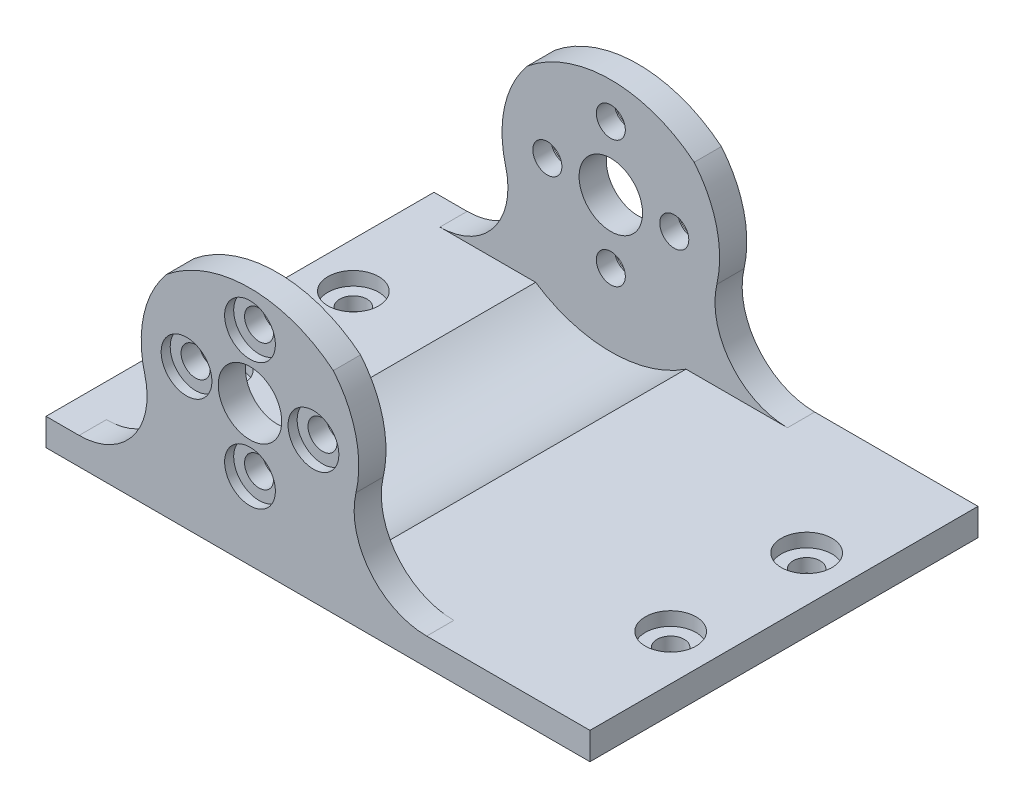
SolidWorks part; units mm, degrees
ref_plane "前视基准面" through (0, 0, 0) normal (0, 0, 1) x (1, 0, 0)
ref_plane "上视基准面" through (0, 0, 0) normal (0, 1, 0) x (1, 0, 0)
ref_plane "右视基准面" through (0, 0, 0) normal (1, 0, 0) x (0, 0, -1)
other "Configuration Table"
sketch "草图1" plane through (0, 0, 0) normal (0, 0, 1) x (1, 0, 0)
  circle A0 centre (0, 0) radius 13
  dimension "D1" = 26
extrude "凸台-拉伸1" add sketch "草图1" along normal blind 42.8
sketch "草图2" plane through (0, 0, 42.8) normal (0, 0, 1) x (1, 0, 0)
  circle A0 centre (0, 0) radius 3.5
  dimension "D1" = 7
extrude "切除-拉伸1" cut sketch "草图2" against normal through all
sketch "草图4" plane through (0, 0, 0) normal (0, 0, -1) x (-1, 0, 0)
  circle A0 centre (0, 0) radius 7 construction
  circle A1 centre (0, 7) radius 1.6
  circle A2 centre (7, 0) radius 1.6
  circle A3 centre (0, -7) radius 1.6
  circle A4 centre (-7, 0) radius 1.6
  point P14 (0, 0)
  dimension "D1" = 14
  dimension "D2" = 3.2
  dimension "D3" = 4
extrude "切除-拉伸2" cut sketch "草图4" against normal through all
sketch "草图5" plane through (0, 0, 0) normal (0, 0, -1) x (-1, 0, 0)
  line L0 (-12.5, 0) -> (-12.5, -12.5) construction
  line L1 (-12.5, -12.5) -> (-37.5, -12.5)
  line L2 (-37.5, -12.5) -> (-37.5, -15.5)
  line L3 (-37.5, -15.5) -> (22.5, -15.5)
  line L4 (22.5, -15.5) -> (22.5, -12.5)
  line L6 (12.5, 0) -> (12.5, -12.5) construction
  line L7 (12.5, -12.5) -> (22.5, -12.5)
  circle A0 centre (0, 0) radius 12.5
  arc A1 (-25, -12.5) -> (-12.5, 0) centre (-25, 0) ccw
  arc A2 (12.5, 0) -> (22.5, -12.5) centre (25.3125, 0) ccw
  dimension "D1" = 25
  dimension "D5" = 12.5
  dimension "D2" = 3
  dimension "D3" = 25
  dimension "D4" = 10
extrude "凸台-拉伸2" add sketch "草图5" against normal up to surface (42.8 mm away) up to face at (-1.6, 7, 42.8)
sketch "草图7" plane through (0, 0, 0) normal (0, 0, -1) x (-1, 0, 0)
  line L4 (-25, -12.5) -> (-37.5, -12.5)
  line L5 (-37.5, -12.5) -> (-37.5, -15.5)
  line L6 (-37.5, -15.5) -> (22.5, -15.5)
  line L7 (22.5, -15.5) -> (22.5, -12.5)
  arc A0 (12.5, 0) -> (-12.5, 0) centre (0, 0) ccw
  arc A1 (-12.755, -2.512) -> (-12.5, 0) centre (-25, 0) ccw
  arc A2 (12.5, 0) -> (12.7519, -2.5279) centre (25.3125, 0) ccw
  arc A4 (12.7519, -2.5279) -> (-12.755, -2.512) centre (0, 0) ccw
  arc A5 (-25, -12.5) -> (-12.755, -2.512) centre (-25, 0) ccw
  arc A6 (12.7519, -2.5279) -> (22.5, -12.5) centre (25.3125, 0) ccw
  arc A7 (12.7519, -2.5279) -> (-12.755, -2.512) centre (0, 0) ccw
  dimension "D1" = 25
  dimension "D2" = 0
extrude "切除-拉伸3" cut sketch "草图7" against normal up to surface (42.8 mm away) contours A7 A1 A0 A2 up to face at (-1.6, 7, 42.8)
ref_plane "基准面1" through (0, 0, 21.4) normal (0, 0, 1) x (1, 0, 0)
sketch "草图8" plane through (0, 0, 21.4) normal (0, 0, 1) x (1, 0, 0)
  line L2 (-22.5, -12.5) -> (25, -12.5) construction
  line L3 (0, -12.5) -> (-22.5, -12.5)
  line L4 (0, -12.5) -> (25, -12.5)
  line L7 (-22.5, -12.5) -> (-22.5, -15.5)
  line L8 (-22.5, -15.5) -> (37.5, -15.5)
  line L9 (37.5, -15.5) -> (37.5, -12.5)
  line L10 (37.5, -12.5) -> (25, -12.5)
  circle A0 centre (0, 0) radius 12.5
  arc A1 (12.5, 0) -> (25, -12.5) centre (25, 0) ccw construction
  arc A2 (-22.5, -12.5) -> (-12.5, 0) centre (-25.3125, 0) ccw construction
  arc A6 (12.5, 0) -> (25, -12.5) centre (25, 0) ccw
  arc A7 (12.5, 0) -> (-12.5, 0) centre (0, 0) ccw
  arc A8 (-22.5, -12.5) -> (-12.5, 0) centre (-25.3125, 0) ccw
  arc A9 (12.5, 0) -> (25, -12.5) centre (25, 0) ccw
  arc A10 (12.5, 0) -> (-12.5, 0) centre (0, 0) ccw
  arc A11 (-22.5, -12.5) -> (-12.5, 0) centre (-25.3125, 0) ccw
  dimension "D2" = 25
  dimension "D4" = 0
extrude "切除-拉伸4" cut sketch "草图8" against normal offset from surface 3 and the other way offset from surface (18.4 mm away) 3 up to face at (-1.6, 7, 0) other way up to face at (7.8005, -8.6204, 42.8)
sketch "草图9" plane through (0, -12.5, 0) normal (0, 1, 0) x (1, 0, 0)
  line L0 (37.5, -21.4) -> (32.5, -21.4) construction
  line L1 (37.5, -42.8) -> (37.5, 0) construction
  line L3 (32.5, -13.9) -> (32.5, -28.9) construction
  line L4 (-22.5, -21.4) -> (-17.5, -21.4) construction
  line L6 (-17.5, -28.9) -> (-17.5, -13.9) construction
  circle A0 centre (32.5, -13.9) radius 1.5
  circle A1 centre (32.5, -28.9) radius 1.5
  circle A2 centre (-17.5, -13.9) radius 1.5
  circle A3 centre (-17.5, -28.9) radius 1.5
  point P9 (32.5, -21.4)
  point P18 (-17.5, -21.4)
  dimension "D3" = 3
  dimension "D4" = 3
  dimension "D7" = 3
  dimension "D8" = 3
  dimension "D1" = 15
  dimension "D2" = 5
  dimension "D5" = 15
  dimension "D6" = 5
extrude "切除-拉伸5" cut sketch "草图9" against normal through all both and the other way through all
sketch "草图10" plane through (0, -12.5, 0) normal (0, 1, 0) x (1, 0, 0)
  circle A0 centre (-17.5, -13.9) radius 2.8
  circle A1 centre (-17.5, -28.9) radius 2.8
  circle A2 centre (32.5, -13.9) radius 2.8
  circle A3 centre (32.5, -28.9) radius 2.8
  dimension "D1" = 5.6
  dimension "D2" = 5.6
  dimension "D3" = 5.6
  dimension "D4" = 5.6
extrude "切除-拉伸6" cut sketch "草图10" against normal blind 1.5 and the other way through all
sketch "草图11" plane through (0, 0, 0) normal (0, 0, -1) x (-1, 0, 0)
  circle A0 centre (0, 7) radius 2.8
  circle A1 centre (7, 0) radius 2.8
  circle A2 centre (0, -7) radius 2.8
  circle A3 centre (-7, 0) radius 2.8
  dimension "D1" = 5.6
  dimension "D2" = 5.6
  dimension "D3" = 5.6
  dimension "D4" = 5.6
extrude "切除-拉伸7" cut sketch "草图11" against normal blind 1
mirror "镜向1" about plane through (0, 0, 21.4) normal (0, 0, 1) of "切除-拉伸7"
sketch "草图12" plane through (0, 0, 21.4) normal (0, 0, 1) x (1, 0, 0)
  line L1 (-22.5, -12.5) -> (25, -12.5)
  line L2 (-8.2916, -12.5) -> (8.2916, -12.5)
  arc A0 (-13.858, -5.7407) -> (13.875, -5.6995) centre (0, 0) ccw
  arc A4 (12.5, 0) -> (-12.5, 0) centre (0, 0) ccw
  arc A5 (-22.5, -12.5) -> (-12.5, 0) centre (-25.3125, 0) ccw
  arc A6 (12.5, 0) -> (25, -12.5) centre (25, 0) ccw
  arc A7 (12.5, 0) -> (-12.5, 0) centre (0, 0) ccw
  arc A8 (-13.858, -5.7407) -> (-12.5, 0) centre (-25.3125, 0) ccw
  arc A9 (12.5, 0) -> (13.875, -5.6995) centre (25, 0) ccw
  dimension "D1" = 30
  dimension "D2" = 0
extrude "切除-拉伸8" cut sketch "草图12" against normal up to surface and the other way up to surface contours L2 A0 up to face at (0.5259, -4.2107, 3) other way up to face at (8.6, 0, 39.8)
sketch "草图13" plane through (0, 0, 0) normal (0, 0, -1) x (-1, 0, 0)
  line L0 (0, 0) -> (0, -7) construction
  line L4 (-25, -12.5) -> (-37.5, -12.5)
  line L5 (-37.5, -12.5) -> (-37.5, -15.5)
  line L6 (-37.5, -15.5) -> (22.5, -15.5)
  line L7 (22.5, -15.5) -> (22.5, -12.5)
  arc A0 (10.9853, 5.9643) -> (-10.9853, 5.9643) centre (0, -3.5) ccw
  circle A1 centre (0, 0) radius 3.5 construction
  arc A5 (12.5, 0) -> (-12.5, 0) centre (0, 0) ccw
  arc A6 (-25, -12.5) -> (-12.5, 0) centre (-25, 0) ccw
  arc A7 (12.5, 0) -> (22.5, -12.5) centre (25.3125, 0) ccw
  arc A8 (10.9853, 5.9643) -> (-10.9853, 5.9643) centre (0, 0) ccw
  point P16 (0, -3.5)
  dimension "D1" = 29
  dimension "D2" = 0
extrude "切除-拉伸9" cut sketch "草图13" against normal through all
sketch "草图14" plane through (0, 0, 42.8) normal (0, 0, 1) x (1, 0, 0)
  line L0 (-22.5, -12.5) -> (25, -12.5)
  line L4 (-22.5, -12.5) -> (-22.5, -15.5)
  line L5 (-22.5, -15.5) -> (37.5, -15.5)
  line L6 (37.5, -15.5) -> (37.5, -12.5)
  line L7 (37.5, -12.5) -> (25, -12.5)
  line L8 (-22.5, -12.5) -> (-22.5, -15.5)
  line L9 (-22.5, -15.5) -> (37.5, -15.5)
  line L10 (37.5, -15.5) -> (37.5, -12.5)
  line L11 (37.5, -12.5) -> (25, -12.5)
  circle A0 centre (0, 0) radius 12
  circle A1 centre (-18.8481, -5) radius 7.5
  circle A2 centre (19.4872, -4.5) radius 8
  arc A6 (10.9853, 5.9643) -> (-10.9853, 5.9643) centre (0, -3.5) ccw
  arc A7 (-10.9853, 5.9643) -> (-12.5, 0) centre (0, 0) ccw
  arc A8 (-22.5, -12.5) -> (-12.5, 0) centre (-25.3125, 0) ccw
  arc A9 (12.5, 0) -> (25, -12.5) centre (25, 0) ccw
  arc A10 (12.5, 0) -> (10.9853, 5.9643) centre (0, 0) ccw
  arc A11 (10.9853, 5.9643) -> (-10.9853, 5.9643) centre (0, -3.5) ccw
  arc A12 (-10.9853, 5.9643) -> (-12.5, 0) centre (0, 0) ccw
  arc A13 (-22.5, -12.5) -> (-12.5, 0) centre (-25.3125, 0) ccw
  arc A14 (12.5, 0) -> (25, -12.5) centre (25, 0) ccw
  arc A15 (12.5, 0) -> (10.9853, 5.9643) centre (0, 0) ccw
  arc M19 (10.9853, 5.9643) -> (-10.9853, 5.9643) centre (0, -3.5) ccw
  arc M20 (-10.9853, 5.9643) -> (-12.5, 0) centre (0, 0) ccw
  arc M21 (-12.5, 0) -> (-22.5, -12.5) centre (-25.3125, 0) cw
  arc M26 (25, -12.5) -> (12.5, 0) centre (25, 0) cw
  arc M27 (12.5, 0) -> (10.9853, 5.9643) centre (0, 0) ccw
  dimension "D1" = 24
  dimension "D3" = 15
  dimension "D4" = 16
  dimension "D2" = 0
extrude "切除-拉伸10" cut sketch "草图14" against normal through all contours A1 M21 | A1 A0 M19 M20 M21 | A1 L0 M21 | A2 L0 M26 | A2 M26 | A2 A0 M26 M27 M19
